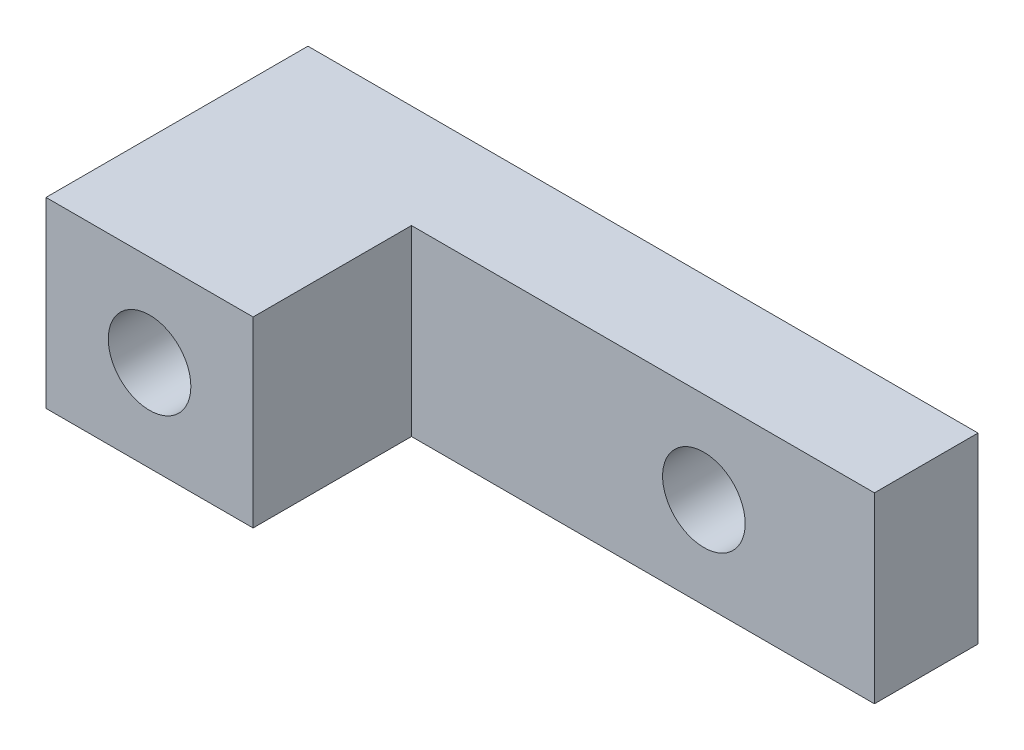
SolidWorks part; units mm, degrees
material "6061-T6 (SS)"
ref_plane "Front Plane" through (0, 0, 0) normal (0, 0, 1) x (1, 0, 0)
ref_plane "Top Plane" through (0, 0, 0) normal (0, 1, 0) x (1, 0, 0)
ref_plane "Right Plane" through (0, 0, 0) normal (1, 0, 0) x (0, 0, -1)
sketch "Sketch1" plane through (0, 0, 0) normal (0, 1, 0) x (1, 0, 0)
  line L0 (0, 0) -> (0, 8.255)
  line L1 (0, 8.255) -> (24.13, 8.255)
  line L2 (24.13, 8.255) -> (24.13, 13.6525)
  line L3 (24.13, 13.6525) -> (-10.795, 13.6525)
  line L4 (-10.795, 13.6525) -> (-10.795, 0)
  line L5 (-10.795, 0) -> (0, 0)
  dimension "D1" = 8.255
  dimension "D2" = 13.6525
  dimension "D3" = 10.795
  dimension "D4" = 34.925
extrude "Boss-Extrude1" add sketch "Sketch1" along normal mid plane 9.525
sketch "Sketch3" plane through (0, 0, 0) normal (0, 0, 1) x (1, 0, 0)
  line L0 (24.13, 4.7625) -> (24.13, -4.7625) construction
  line L1 (-10.795, 4.7625) -> (-10.795, -4.7625) construction
  circle A0 centre (15.24, 0) radius 2.1527
  circle A1 centre (-5.3975, 0) radius 2.1527
  dimension "D1" = 4.3053
  dimension "D2" = 8.89
  dimension "D3" = 5.3975
extrude "Cut-Extrude1" cut sketch "Sketch3" against normal through all
